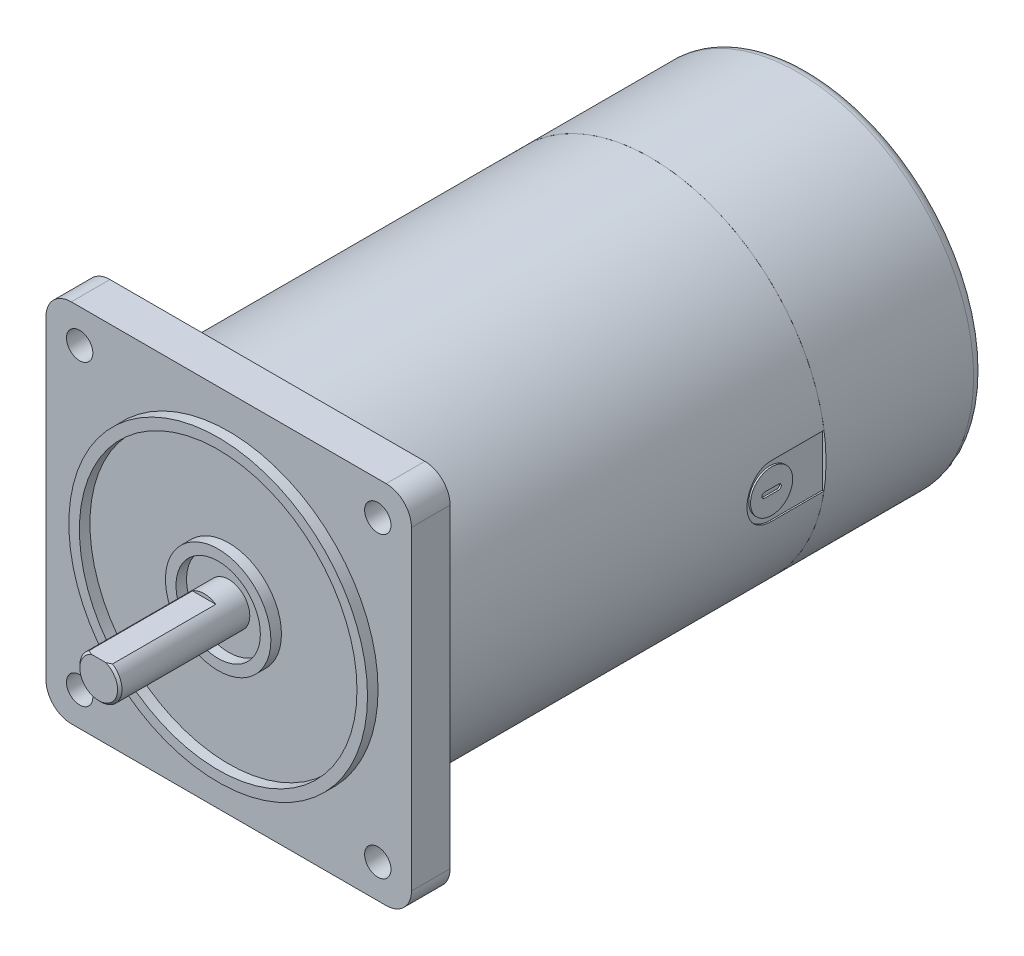
SolidWorks part; units mm, degrees
ref_plane "前视基准面" through (0, 0, 0) normal (0, 0, 1) x (1, 0, 0)
ref_plane "上视基准面" through (0, 0, 0) normal (0, 1, 0) x (1, 0, 0)
ref_plane "右视基准面" through (0, 0, 0) normal (1, 0, 0) x (0, 0, -1)
sketch "草图1" plane through (0, 0, 0) normal (0, 0, 1) x (1, 0, 0)
  line L0 (0, 0) -> (165, 0)
  line L1 (165, 0) -> (165, 50)
  line L2 (165, 50) -> (120, 50)
  line L3 (120, 50) -> (120, 42.5)
  line L4 (120, 42.5) -> (119.99, 42.5)
  line L5 (119.99, 42.5) -> (119.99, 50)
  line L6 (119.99, 50) -> (11, 50)
  line L7 (0, 52) -> (0, 6)
  line L8 (0, 42.5) -> (-3, 42.5)
  line L9 (-3, 42.5) -> (-3, 39.5)
  line L10 (-3, 39.5) -> (0, 39.5)
  line L11 (0, 15) -> (-3, 15)
  line L12 (-3, 15) -> (-3, 12)
  line L13 (-3, 12) -> (0, 12)
  line L14 (0, 6) -> (-37, 6)
  line L15 (-37, 6) -> (-37, 0)
  line L16 (-37, 0) -> (0, 0) construction
  line L17 (0, 52) -> (11, 52)
  line L18 (11, 52) -> (11, 50)
  line L19 (0, 60) -> (11, 60) construction
  point P19 (-7, 6)
  point P21 (11, 50)
  point P26 (0, 63.75)
  point P27 (-37, -5)
  dimension "D1" = 12
  dimension "D2" = 37
  dimension "D3" = 30
  dimension "D4" = 3
  dimension "D5" = 85
  dimension "D6" = 100
  dimension "D7" = 3
  dimension "D8" = 30
  dimension "D9" = 11
  dimension "D10" = 165
  dimension "D11" = 45
  dimension "D12" = 0.01
  dimension "D13" = 104
  dimension "D14" = 120
  dimension "D15" = 7.5
  dimension "D16" = 11
sketch "草图2" plane through (0, 0, 0) normal (0, 0, 1) x (1, 0, 0)
  line L0 (0, 15) -> (-3, 15) construction
  line L1 (-3, 15) -> (-3, 12) construction
  line L2 (-3, 12) -> (0, 12) construction
  line L3 (0, 42.5) -> (-3, 42.5) construction
  line L4 (-3, 42.5) -> (-3, 39.5) construction
  line L5 (-3, 39.5) -> (0, 39.5) construction
  line L6 (0, 0) -> (165, 0) construction
  line L7 (165, 0) -> (165, 50) construction
  line L8 (165, 50) -> (120, 50) construction
  line L9 (120, 50) -> (120, 42.5) construction
  line L10 (120, 42.5) -> (119.99, 42.5) construction
  line L11 (119.99, 42.5) -> (119.99, 50) construction
  line L13 (0, 52) -> (0, 6) construction
  line L14 (0, 6) -> (-37, 6) construction
  line L15 (-37, 6) -> (-37, 0) construction
  line L16 (0, 15) -> (-3, 15)
  line L17 (-3, 15) -> (-3, 12)
  line L18 (-3, 12) -> (0, 12)
  line L19 (0, 42.5) -> (-3, 42.5)
  line L20 (-3, 42.5) -> (-3, 39.5)
  line L21 (-3, 39.5) -> (0, 39.5)
  line L22 (-37, 0) -> (165, 0)
  line L23 (165, 0) -> (165, 50)
  line L24 (165, 50) -> (120, 50)
  line L25 (120, 50) -> (120, 42.5)
  line L26 (120, 42.5) -> (119.99, 42.5)
  line L27 (119.99, 42.5) -> (119.99, 50)
  line L28 (119.99, 50) -> (0, 50)
  line L29 (0, 50) -> (0, 42.5)
  line L30 (0, 6) -> (-37, 6)
  line L31 (-37, 6) -> (-37, 0)
  line L32 (0, 39.5) -> (0, 15)
  line L33 (0, 12) -> (0, 6)
revolve "旋转1" add sketch "草图2" angle 360 about L22
sketch "草图3" plane through (0, 0, 0) normal (-1, 0, 0) x (0, 0, 1)
  line L1 (-52, 52) -> (52, 52)
  line L2 (-52, 52) -> (-52, -52)
  line L3 (-52, -52) -> (52, -52)
  line L4 (52, 52) -> (52, -52)
  dimension "D1" = 104
extrude "凸台-拉伸1" add sketch "草图3" against normal up to vertex (11 mm away) up to point (11, 50, 0)
sketch "草图4" plane through (0, 0, 0) normal (-1, 0, 0) x (0, 0, 1)
  line L0 (42.4264, 42.4264) -> (0, 0) construction
  line L1 (0, 0) -> (0, 50) construction
  circle A0 centre (0, 0) radius 60 construction
  circle A1 centre (42.4264, 42.4264) radius 3.75
  dimension "D2" = 7.5
  dimension "D3" = 45
extrude "切除-拉伸1" cut sketch "草图4" against normal up to vertex (11 mm away)
pattern_circular "阵列(圆周)1" count 4 over 360 about axis through (0, 0, 0) along (1, 0, 0) of "切除-拉伸1"
fillet "圆角1" radius 7.2 4 edges at (5.5, -52, 52) (5.5, -52, -52) (5.5, 52, -52) (5.5, 52, 52)
sketch "草图5" plane through (-37, 0, 0) normal (-1, 0, 0) x (0, 0, 1)
  line L0 (-3.3166, 5) -> (3.3166, 5)
  line L1 (3.3166, 5) -> (3.3166, 6)
  line L2 (3.3166, 6) -> (-3.3166, 6)
  line L3 (-3.3166, 6) -> (-3.3166, 5)
  circle A0 centre (0, 0) radius 6 construction
  circle A1 centre (0, 0) radius 6 construction
  point P2 (0, -6)
  dimension "D1" = 11
extrude "切除-拉伸2" cut sketch "草图5" against normal up to vertex (30 mm away) up to point (-7, 6, 0)
fillet "圆角2" radius 3 1 edges at (165, 0, 50)
sketch "草图6" plane through (0, 0, 0) normal (0, 0, 1) x (1, 0, 0)
  line L0 (0, 0) -> (165, 0) construction
  line L1 (105, 7.5) -> (120, 7.5)
  line L2 (105, 7.5) -> (105, -7.5) construction
  line L3 (105, -7.5) -> (120, -7.5)
  line L4 (120, 7.5) -> (120, -7.5)
  arc A0 (105, 7.5) -> (105, -7.5) centre (105, 0) ccw
  point P4 (105, 0)
  dimension "D2" = 15
  dimension "D1" = 15
extrude "切除-拉伸3" cut sketch "草图6" against normal blind 1 from offset 50
sketch "草图7" plane through (0, 0, 49) normal (0, 0, 1) x (1, 0, 0)
  line L0 (103, 0) -> (107, 0) construction
  line L1 (0, 0) -> (165, 0) construction
  line L2 (103, 0.75) -> (107, 0.75)
  line L3 (103, -0.75) -> (107, -0.75)
  circle A0 centre (105, 0) radius 6
  arc A1 (103, 0.75) -> (103, -0.75) centre (103, 0) ccw
  arc A2 (107, -0.75) -> (107, 0.75) centre (107, 0) ccw
  point P7 (105, 0)
  dimension "D1" = 12
  dimension "D2" = 4
  dimension "D3" = 1.5
extrude "凸台-拉伸2" add sketch "草图7" along normal blind 0.5
chamfer "倒角2" distance 0.62 angle 45 1 edges at (-37, -6, 0)
move or copy body "实体-移动/复制1" bodies to move or copy 107 copy no rotation origin (0, 0, 0) rotation axis (0, 1, 0) rotation angle 90
